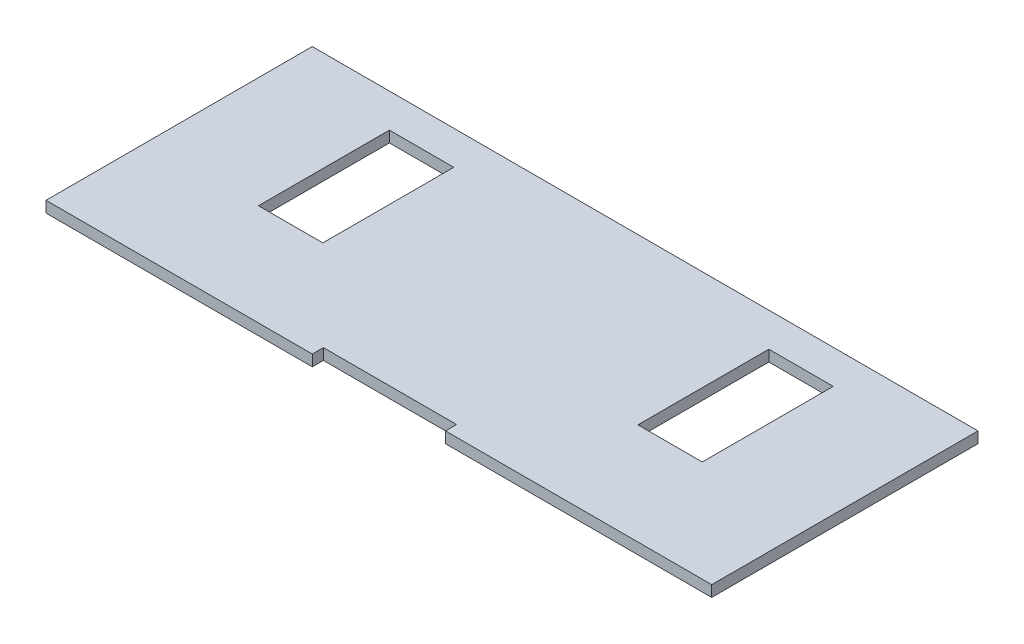
SolidWorks part; units mm, degrees
ref_plane "Front Plane" through (0, 0, 0) normal (0, 0, 1) x (1, 0, 0)
ref_plane "Top Plane" through (0, 0, 0) normal (0, 1, 0) x (1, 0, 0)
ref_plane "Right Plane" through (0, 0, 0) normal (1, 0, 0) x (0, 0, -1)
sketch "Sketch1" plane through (0, 0, 0) normal (0, 1, 0) x (1, 0, 0)
  line L1 (-300, 120) -> (0, 120)
  line L2 (-300, 120) -> (-300, 0)
  line L3 (-300, 0) -> (0, 0)
  line L4 (0, 120) -> (0, 0)
  dimension "D1" = 300
  dimension "D2" = 120
extrude "Boss-Extrude1" add sketch "Sketch1" along normal blind 5
sketch "Sketch2" plane through (0, 5, 0) normal (0, 1, 0) x (1, 0, 0)
  line L0 (0, 120) -> (-300, 120) construction
  line L1 (-50, 45.75) -> (-79, 45.75)
  line L2 (-50, 45.75) -> (-50, 104.75)
  line L3 (-50, 104.75) -> (-79, 104.75)
  line L4 (-79, 45.75) -> (-79, 104.75)
  line L5 (-221, 45.75) -> (-250, 45.75)
  line L6 (-221, 45.75) -> (-221, 104.75)
  line L7 (-221, 104.75) -> (-250, 104.75)
  line L8 (-250, 45.75) -> (-250, 104.75)
  line L9 (0, 0) -> (0, 120) construction
  line L10 (-300, 120) -> (-300, 0) construction
  line L11 (-300, 0) -> (0, 0) construction
  line L12 (-120, 0) -> (-180, 0)
  line L13 (-120, 0) -> (-120, 5)
  line L14 (-120, 5) -> (-180, 5)
  line L15 (-180, 0) -> (-180, 5)
  dimension "D1" = 59
  dimension "D2" = 29
  dimension "D3" = 15.25
  dimension "D4" = 50
  dimension "D5" = 29
  dimension "D6" = 59
  dimension "D7" = 50
  dimension "D8" = 15.25
  dimension "D9" = 5
  dimension "D10" = 60
  dimension "D11" = 120
extrude "Cut-Extrude1" cut sketch "Sketch2" against normal blind 5
